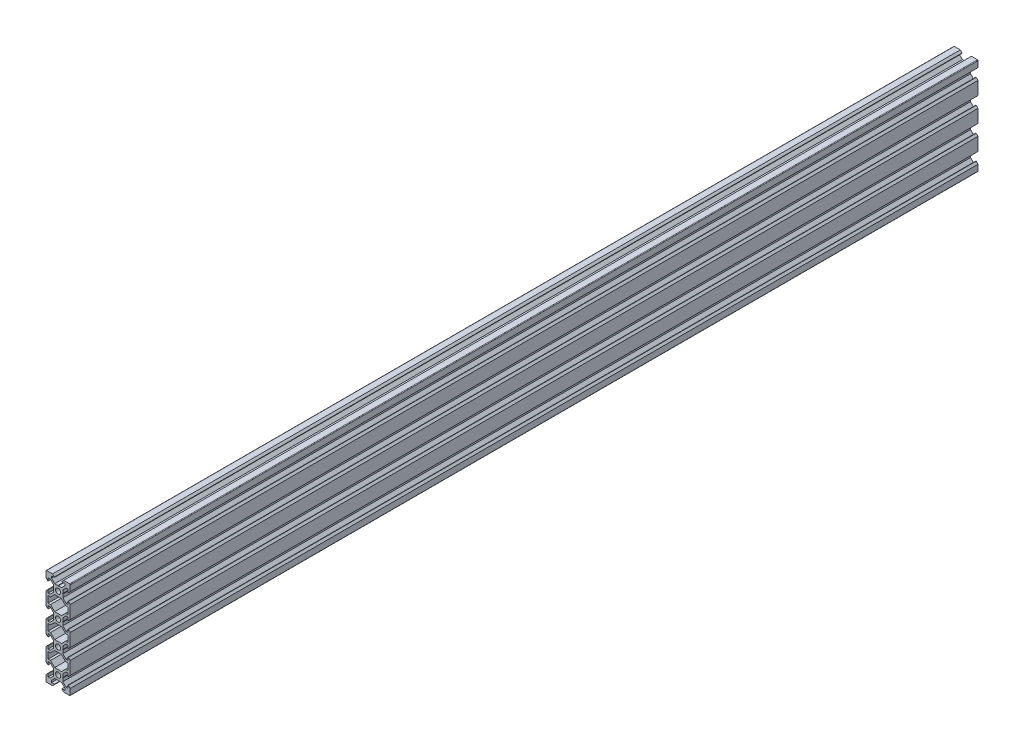
SolidWorks part; units mm, degrees
material "6061-T6 (SS)"
ref_plane "Front Plane" through (0, 0, 0) normal (0, 0, 1) x (1, 0, 0)
ref_plane "Top Plane" through (0, 0, 0) normal (0, 1, 0) x (1, 0, 0)
ref_plane "Right Plane" through (0, 0, 0) normal (1, 0, 0) x (0, 0, -1)
sketch "Sketch1" plane through (0, 0, 0) normal (0, 0, 1) x (1, 0, 0)
  line L0 (0, 0) -> (10, 0) construction
  line L1 (9.5, -40) -> (-9.5, -40)
  line L2 (10, -39.5) -> (10, 39.5)
  line L3 (9.5, 40) -> (-9.5, 40)
  line L4 (-10, -39.5) -> (-10, 39.5)
  line L5 (10, -40) -> (-10, 40) construction
  line L6 (10, 40) -> (-10, -40) construction
  circle A0 centre (0, 30) radius 2.1
  circle A1 centre (0, 10) radius 2.1
  circle A2 centre (0, -10) radius 2.1
  circle A3 centre (0, -30) radius 2.1
  arc A4 (-9.5, -40) -> (-10, -39.5) centre (-9.5, -39.5) cw
  arc A5 (9.5, -40) -> (10, -39.5) centre (9.5, -39.5) ccw
  arc A6 (10, 39.5) -> (9.5, 40) centre (9.5, 39.5) ccw
  arc A7 (-9.5, 40) -> (-10, 39.5) centre (-9.5, 39.5) ccw
  point P0 (0, 0)
  line B0 (0, 30) -> (0, 40) construction
  line B1 (0, 33.69) -> (-0.21, 33.9)
  line B2 (-0.21, 33.9) -> (-2.8393, 33.9)
  line B3 (-2.8393, 33.9) -> (-5.5, 36.5607)
  line B4 (-5.5, 36.5607) -> (-5.5, 38.2)
  line B5 (-5.5, 38.2) -> (-3.125, 38.2)
  line B6 (-3.125, 38.2) -> (-3.125, 38.545)
  line B7 (-3.125, 38.545) -> (-4.58, 40)
  line B8 (-4.58, 40) -> (4.58, 40)
  line B9 (0, 30) -> (-5.9132, 35.9132) construction
  line B10 (3.125, 38.545) -> (4.58, 40)
  line B11 (3.125, 38.2) -> (3.125, 38.545)
  line B12 (5.5, 38.2) -> (3.125, 38.2)
  line B13 (5.5, 36.5607) -> (5.5, 38.2)
  line B14 (2.8393, 33.9) -> (5.5, 36.5607)
  line B15 (0.21, 33.9) -> (2.8393, 33.9)
  line B16 (0, 33.69) -> (0.21, 33.9)
  line B17 (0, 30) -> (-10, 30) construction
  line B18 (-3.69, 30) -> (-3.9, 29.79)
  line B19 (-3.9, 29.79) -> (-3.9, 27.1607)
  line B20 (-3.9, 27.1607) -> (-6.5607, 24.5)
  line B21 (-6.5607, 24.5) -> (-8.2, 24.5)
  line B22 (-8.2, 24.5) -> (-8.2, 26.875)
  line B23 (-8.2, 26.875) -> (-8.545, 26.875)
  line B24 (-8.545, 26.875) -> (-10, 25.42)
  line B25 (-10, 25.42) -> (-10, 34.58)
  line B26 (0, 30) -> (-5.9132, 24.0868) construction
  line B27 (-8.545, 33.125) -> (-10, 34.58)
  line B28 (-8.2, 33.125) -> (-8.545, 33.125)
  line B29 (-8.2, 35.5) -> (-8.2, 33.125)
  line B30 (-6.5607, 35.5) -> (-8.2, 35.5)
  line B31 (-3.9, 32.8393) -> (-6.5607, 35.5)
  line B32 (-3.9, 30.21) -> (-3.9, 32.8393)
  line B33 (-3.69, 30) -> (-3.9, 30.21)
  line B34 (0, 10) -> (-10, 10) construction
  line B35 (-3.69, 10) -> (-3.9, 9.79)
  line B36 (-3.9, 9.79) -> (-3.9, 7.1607)
  line B37 (-3.9, 7.1607) -> (-6.5607, 4.5)
  line B38 (-6.5607, 4.5) -> (-8.2, 4.5)
  line B39 (-8.2, 4.5) -> (-8.2, 6.875)
  line B40 (-8.2, 6.875) -> (-8.545, 6.875)
  line B41 (-8.545, 6.875) -> (-10, 5.42)
  line B42 (-10, 5.42) -> (-10, 14.58)
  line B43 (0, 10) -> (-5.9132, 4.0868) construction
  line B44 (-8.545, 13.125) -> (-10, 14.58)
  line B45 (-8.2, 13.125) -> (-8.545, 13.125)
  line B46 (-8.2, 15.5) -> (-8.2, 13.125)
  line B47 (-6.5607, 15.5) -> (-8.2, 15.5)
  line B48 (-3.9, 12.8393) -> (-6.5607, 15.5)
  line B49 (-3.9, 10.21) -> (-3.9, 12.8393)
  line B50 (-3.69, 10) -> (-3.9, 10.21)
  line B51 (0, -10) -> (-10, -10) construction
  line B52 (-3.69, -10) -> (-3.9, -10.21)
  line B53 (-3.9, -10.21) -> (-3.9, -12.8393)
  line B54 (-3.9, -12.8393) -> (-6.5607, -15.5)
  line B55 (-6.5607, -15.5) -> (-8.2, -15.5)
  line B56 (-8.2, -15.5) -> (-8.2, -13.125)
  line B57 (-8.2, -13.125) -> (-8.545, -13.125)
  line B58 (-8.545, -13.125) -> (-10, -14.58)
  line B59 (-10, -14.58) -> (-10, -5.42)
  line B60 (0, -10) -> (-5.9132, -15.9132) construction
  line B61 (-8.545, -6.875) -> (-10, -5.42)
  line B62 (-8.2, -6.875) -> (-8.545, -6.875)
  line B63 (-8.2, -4.5) -> (-8.2, -6.875)
  line B64 (-6.5607, -4.5) -> (-8.2, -4.5)
  line B65 (-3.9, -7.1607) -> (-6.5607, -4.5)
  line B66 (-3.9, -9.79) -> (-3.9, -7.1607)
  line B67 (-3.69, -10) -> (-3.9, -9.79)
  line B68 (0, -30) -> (-10, -30) construction
  line B69 (-3.69, -30) -> (-3.9, -30.21)
  line B70 (-3.9, -30.21) -> (-3.9, -32.8393)
  line B71 (-3.9, -32.8393) -> (-6.5607, -35.5)
  line B72 (-6.5607, -35.5) -> (-8.2, -35.5)
  line B73 (-8.2, -35.5) -> (-8.2, -33.125)
  line B74 (-8.2, -33.125) -> (-8.545, -33.125)
  line B75 (-8.545, -33.125) -> (-10, -34.58)
  line B76 (-10, -34.58) -> (-10, -25.42)
  line B77 (0, -30) -> (-5.9132, -35.9132) construction
  line B78 (-8.545, -26.875) -> (-10, -25.42)
  line B79 (-8.2, -26.875) -> (-8.545, -26.875)
  line B80 (-8.2, -24.5) -> (-8.2, -26.875)
  line B81 (-6.5607, -24.5) -> (-8.2, -24.5)
  line B82 (-3.9, -27.1607) -> (-6.5607, -24.5)
  line B83 (-3.9, -29.79) -> (-3.9, -27.1607)
  line B84 (-3.69, -30) -> (-3.9, -29.79)
  line B85 (0, -30) -> (0, -40) construction
  line B86 (0, -33.69) -> (0.21, -33.9)
  line B87 (0.21, -33.9) -> (2.8393, -33.9)
  line B88 (2.8393, -33.9) -> (5.5, -36.5607)
  line B89 (5.5, -36.5607) -> (5.5, -38.2)
  line B90 (5.5, -38.2) -> (3.125, -38.2)
  line B91 (3.125, -38.2) -> (3.125, -38.545)
  line B92 (3.125, -38.545) -> (4.58, -40)
  line B93 (4.58, -40) -> (-4.58, -40)
  line B94 (0, -30) -> (5.9132, -35.9132) construction
  line B95 (-3.125, -38.545) -> (-4.58, -40)
  line B96 (-3.125, -38.2) -> (-3.125, -38.545)
  line B97 (-5.5, -38.2) -> (-3.125, -38.2)
  line B98 (-5.5, -36.5607) -> (-5.5, -38.2)
  line B99 (-2.8393, -33.9) -> (-5.5, -36.5607)
  line B100 (-0.21, -33.9) -> (-2.8393, -33.9)
  line B101 (0, -33.69) -> (-0.21, -33.9)
  line B102 (0, -30) -> (10, -30) construction
  line B103 (3.69, -30) -> (3.9, -29.79)
  line B104 (3.9, -29.79) -> (3.9, -27.1607)
  line B105 (3.9, -27.1607) -> (6.5607, -24.5)
  line B106 (6.5607, -24.5) -> (8.2, -24.5)
  line B107 (8.2, -24.5) -> (8.2, -26.875)
  line B108 (8.2, -26.875) -> (8.545, -26.875)
  line B109 (8.545, -26.875) -> (10, -25.42)
  line B110 (10, -25.42) -> (10, -34.58)
  line B111 (0, -30) -> (5.9132, -24.0868) construction
  line B112 (8.545, -33.125) -> (10, -34.58)
  line B113 (8.2, -33.125) -> (8.545, -33.125)
  line B114 (8.2, -35.5) -> (8.2, -33.125)
  line B115 (6.5607, -35.5) -> (8.2, -35.5)
  line B116 (3.9, -32.8393) -> (6.5607, -35.5)
  line B117 (3.9, -30.21) -> (3.9, -32.8393)
  line B118 (3.69, -30) -> (3.9, -30.21)
  line B119 (0, -10) -> (10, -10) construction
  line B120 (3.69, -10) -> (3.9, -9.79)
  line B121 (3.9, -9.79) -> (3.9, -7.1607)
  line B122 (3.9, -7.1607) -> (6.5607, -4.5)
  line B123 (6.5607, -4.5) -> (8.2, -4.5)
  line B124 (8.2, -4.5) -> (8.2, -6.875)
  line B125 (8.2, -6.875) -> (8.545, -6.875)
  line B126 (8.545, -6.875) -> (10, -5.42)
  line B127 (10, -5.42) -> (10, -14.58)
  line B128 (0, -10) -> (5.9132, -4.0868) construction
  line B129 (8.545, -13.125) -> (10, -14.58)
  line B130 (8.2, -13.125) -> (8.545, -13.125)
  line B131 (8.2, -15.5) -> (8.2, -13.125)
  line B132 (6.5607, -15.5) -> (8.2, -15.5)
  line B133 (3.9, -12.8393) -> (6.5607, -15.5)
  line B134 (3.9, -10.21) -> (3.9, -12.8393)
  line B135 (3.69, -10) -> (3.9, -10.21)
  line B136 (0, 10) -> (10, 10) construction
  line B137 (3.69, 10) -> (3.9, 10.21)
  line B138 (3.9, 10.21) -> (3.9, 12.8393)
  line B139 (3.9, 12.8393) -> (6.5607, 15.5)
  line B140 (6.5607, 15.5) -> (8.2, 15.5)
  line B141 (8.2, 15.5) -> (8.2, 13.125)
  line B142 (8.2, 13.125) -> (8.545, 13.125)
  line B143 (8.545, 13.125) -> (10, 14.58)
  line B144 (10, 14.58) -> (10, 5.42)
  line B145 (0, 10) -> (5.9132, 15.9132) construction
  line B146 (8.545, 6.875) -> (10, 5.42)
  line B147 (8.2, 6.875) -> (8.545, 6.875)
  line B148 (8.2, 4.5) -> (8.2, 6.875)
  line B149 (6.5607, 4.5) -> (8.2, 4.5)
  line B150 (3.9, 7.1607) -> (6.5607, 4.5)
  line B151 (3.9, 9.79) -> (3.9, 7.1607)
  line B152 (3.69, 10) -> (3.9, 9.79)
  line B153 (0, 30) -> (10, 30) construction
  line B154 (3.69, 30) -> (3.9, 30.21)
  line B155 (3.9, 30.21) -> (3.9, 32.8393)
  line B156 (3.9, 32.8393) -> (6.5607, 35.5)
  line B157 (6.5607, 35.5) -> (8.2, 35.5)
  line B158 (8.2, 35.5) -> (8.2, 33.125)
  line B159 (8.2, 33.125) -> (8.545, 33.125)
  line B160 (8.545, 33.125) -> (10, 34.58)
  line B161 (10, 34.58) -> (10, 25.42)
  line B162 (0, 30) -> (5.9132, 35.9132) construction
  line B163 (8.545, 26.875) -> (10, 25.42)
  line B164 (8.2, 26.875) -> (8.545, 26.875)
  line B165 (8.2, 24.5) -> (8.2, 26.875)
  line B166 (6.5607, 24.5) -> (8.2, 24.5)
  line B167 (3.9, 27.1607) -> (6.5607, 24.5)
  line B168 (3.9, 29.79) -> (3.9, 27.1607)
  line B169 (3.69, 30) -> (3.9, 29.79)
  line B170 (-8.2, 17.3) -> (-8.2, 22.7)
  line B171 (-8.2, 22.7) -> (-6.2393, 22.7)
  line B172 (-6.2393, 22.7) -> (-2.8393, 26.1)
  line B173 (-2.8393, 26.1) -> (2.8393, 26.1)
  line B174 (0, 26.1) -> (0, 20) construction
  line B175 (0, 20) -> (-8.2, 20) construction
  line B176 (6.2393, 22.7) -> (2.8393, 26.1)
  line B177 (8.2, 22.7) -> (6.2393, 22.7)
  line B178 (8.2, 17.3) -> (8.2, 22.7)
  line B179 (8.2, 17.3) -> (6.2393, 17.3)
  line B180 (6.2393, 17.3) -> (2.8393, 13.9)
  line B181 (-2.8393, 13.9) -> (2.8393, 13.9)
  line B182 (-6.2393, 17.3) -> (-2.8393, 13.9)
  line B183 (-8.2, 17.3) -> (-6.2393, 17.3)
  line B184 (0, 26.1) -> (0, 30) construction
  line B185 (0, 30) -> (-5.0927, 24.9073) construction
  line B186 (-8.2, -2.7) -> (-8.2, 2.7)
  line B187 (-8.2, 2.7) -> (-6.2393, 2.7)
  line B188 (-6.2393, 2.7) -> (-2.8393, 6.1)
  line B189 (-2.8393, 6.1) -> (2.8393, 6.1)
  line B190 (0, 6.1) -> (0, 0) construction
  line B191 (0, 0) -> (-8.2, 0) construction
  line B192 (6.2393, 2.7) -> (2.8393, 6.1)
  line B193 (8.2, 2.7) -> (6.2393, 2.7)
  line B194 (8.2, -2.7) -> (8.2, 2.7)
  line B195 (8.2, -2.7) -> (6.2393, -2.7)
  line B196 (6.2393, -2.7) -> (2.8393, -6.1)
  line B197 (-2.8393, -6.1) -> (2.8393, -6.1)
  line B198 (-6.2393, -2.7) -> (-2.8393, -6.1)
  line B199 (-8.2, -2.7) -> (-6.2393, -2.7)
  line B200 (0, 6.1) -> (0, 10) construction
  line B201 (0, 10) -> (-5.0927, 4.9073) construction
  line B202 (-8.2, -22.7) -> (-8.2, -17.3)
  line B203 (-8.2, -17.3) -> (-6.2393, -17.3)
  line B204 (-6.2393, -17.3) -> (-2.8393, -13.9)
  line B205 (-2.8393, -13.9) -> (2.8393, -13.9)
  line B206 (0, -13.9) -> (0, -20) construction
  line B207 (0, -20) -> (-8.2, -20) construction
  line B208 (6.2393, -17.3) -> (2.8393, -13.9)
  line B209 (8.2, -17.3) -> (6.2393, -17.3)
  line B210 (8.2, -22.7) -> (8.2, -17.3)
  line B211 (8.2, -22.7) -> (6.2393, -22.7)
  line B212 (6.2393, -22.7) -> (2.8393, -26.1)
  line B213 (-2.8393, -26.1) -> (2.8393, -26.1)
  line B214 (-6.2393, -22.7) -> (-2.8393, -26.1)
  line B215 (-8.2, -22.7) -> (-6.2393, -22.7)
  line B216 (0, -13.9) -> (0, -10) construction
  line B217 (0, -10) -> (-5.0927, -15.0927) construction
  dimension "D5" = 4.2
  dimension "D6" = 0.5
  dimension "D1" = 20
  dimension "D2" = 80
  dimension "D3" = 20
  dimension "D4" = 20
sketch_block_instance "V Slot 1-4"
sketch_block "V Slot 1" parameters "D1"=10, "D2"=11, "D3"=4.3, "D4"=1.8, "D5"=0.21, "D6"=45, "D7"=9.16, "D8"=1.5, "D9"=6.25
sketch_block_instance "V Slot 1-5"
sketch_block_instance "V Slot 1-6"
sketch_block_instance "V Slot 1-7"
sketch_block_instance "V Slot 1-8"
sketch_block_instance "V Slot 1-9"
sketch_block_instance "V Slot 1-10"
sketch_block_instance "V Slot 1-11"
sketch_block_instance "V Slot 1-12"
sketch_block_instance "V Slot 1-13"
sketch_block_instance "Center Cutout 1-1"
sketch_block "Center Cutout 1" parameters "D1"=5.4, "D2"=12.2, "D3"=8.2, "D4"=45, "D5"=10, "D6"=1.5
sketch_block_instance "Center Cutout 1-2"
sketch_block_instance "Center Cutout 1-3"
extrude "Boss-Extrude1" add sketch "Sketch1" along normal blind 750 contours B169 B154 B155 B156 B157 B158 B159 B160 L2 A6 L3 B10 B11 B12 B13 B14 B15 B16 B1 B2 B3 B4 B5 B6 B7 A7 L4 B27 B28 B29 B30 B31 B32 B33 B18 B19 B20 B21 B22 B23 B24 B44 B45 B46 B47 B48 B49 B50 B35
